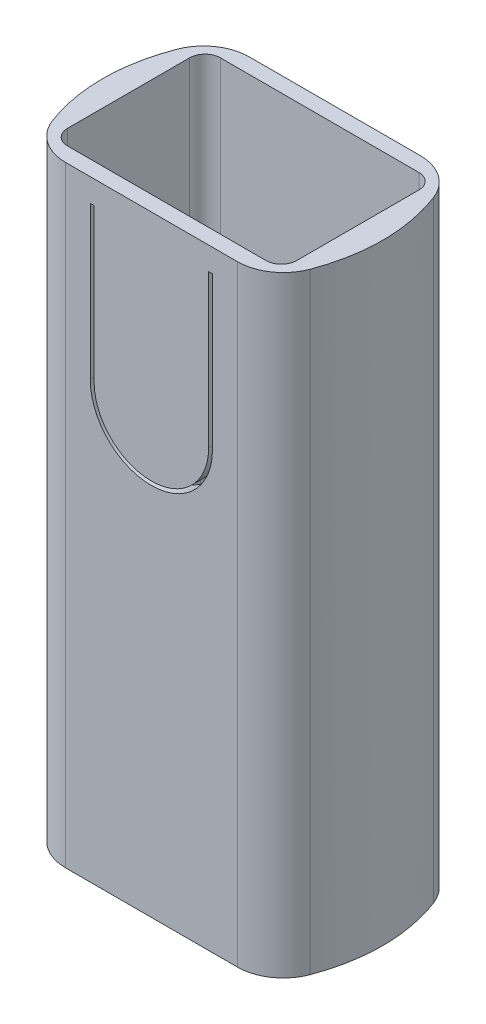
SolidWorks part; units mm, degrees
ref_plane "Front Plane" through (0, 0, 0) normal (0, 0, 1) x (1, 0, 0)
ref_plane "Top Plane" through (0, 0, 0) normal (0, 1, 0) x (1, 0, 0)
ref_plane "Right Plane" through (0, 0, 0) normal (1, 0, 0) x (0, 0, -1)
ref_plane "Plane1" through (0, 58, 0) normal (0, 1, 0) x (1, 0, 0)
sketch "Sketch8" plane through (0, 58, 0) normal (0, 1, 0) x (1, 0, 0)
  line L0 (-13, -10) -> (13, -10)
  line L1 (-15, -8) -> (-15, 8)
  line L2 (-13, 10) -> (13, 10)
  line L3 (15, -8) -> (15, 8)
  line L5 (-15, 10) -> (0, 0) construction
  line L6 (-11.243, -12) -> (11.243, -12)
  line L8 (-11.1948, 12) -> (11.1948, 12)
  line L11 (-17, 12) -> (-13.8786, 9.7967) construction
  line L12 (0, -12) -> (0, 12) construction
  line L15 (0, 12) -> (0, -10) construction
  line L16 (14.2911, -9.5274) -> (15, -10) construction
  line L17 (0, 0) -> (17, -12) construction
  arc A0 (15, -8) -> (13, -10) centre (13, -8) cw
  arc A1 (-15, -8) -> (-13, -10) centre (-13, -8) ccw
  arc A8 (-13, 10) -> (-15, 8) centre (-13, 8) ccw
  arc A9 (13, 10) -> (15, 8) centre (13, 8) cw
  arc A10 (-11.1948, 12) -> (-16.8117, 8.1097) centre (-11.1948, 6) ccw
  arc A11 (-11.243, -12) -> (-16.8596, -8.1104) centre (-11.243, -6) cw
  arc A12 (11.1948, 12) -> (16.8117, 8.1097) centre (11.1948, 6) cw
  arc A13 (11.243, -12) -> (16.8596, -8.1104) centre (11.243, -6) ccw
  spline S0 degree 3 poles (-16.8596, -8.1104) (-17.8507, -5.4727) (-18.8343, 0.0284) (-17.8195, 5.4265) (-16.8117, 8.1097) knots 0.167422 0.167422 0.167422 0.167422 0.502499 0.837905 0.837905 0.837905 0.837905
  spline S1 degree 3 poles (16.8596, -8.1104) (17.8507, -5.4727) (18.8343, 0.0284) (17.8195, 5.4265) (16.8117, 8.1097) knots 0.167422 0.167422 0.167422 0.167422 0.502499 0.837905 0.837905 0.837905 0.837905
  point P0 (0, 0)
  point P19 (-15, 10)
  point P26 (0, 0)
  point P27 (-12, 9.5)
  point P28 (15, 10)
  dimension "D3" = 2
  dimension "D2" = 6
  dimension "D7" = 2
  dimension "D1" = 30
  dimension "D4" = 24
  dimension "D5" = 20
sketch "Sketch11" plane through (0, 58, 0) normal (0, 1, 0) x (1, 0, 0)
  line L10 (-13, 10) -> (13, 10) construction
  line L11 (13, 10) -> (15, 10)
  line L13 (-13, 7.4379) -> (-13, 10)
  line L14 (0, 12) -> (0, -10) construction
  line L19 (15, 10) -> (15, 6.9379)
  line L20 (15, 6.9379) -> (13.5, 6.9379)
  line L21 (13, 7.4379) -> (13, 10)
  line L22 (-15, 6.9379) -> (-13.5, 6.9379)
  line L23 (-15, 10) -> (-15, 6.9379)
  line L24 (-13, 10) -> (-15, 10)
  arc A4 (13.5, 6.9379) -> (13, 7.4379) centre (13.5, 7.4379) cw
  arc A5 (-13.5, 6.9379) -> (-13, 7.4379) centre (-13.5, 7.4379) ccw
  dimension "D1" = 0.5
extrude "Boss-Extrude4" add sketch "Sketch8" along normal blind 80
extrude "Boss-Extrude5" add sketch "Sketch11" along normal blind 57
sketch "Sketch12" plane through (0, 0, 12) normal (0, 0, 1) x (1, 0, 0)
  line L0 (0, 138) -> (0, 58) construction
  line L1 (-11.243, 138) -> (11.243, 138) construction
  line L2 (55, 58) -> (-55, 58) construction
  line L3 (0, 116.5243) -> (0, 136.5243) construction
  line L5 (7.4764, 134.9866) -> (7.4764, 114.9866)
  line L7 (-7.5236, 134.9866) -> (-7.5236, 114.9866)
  line L8 (7.4764, 134.9866) -> (7.9764, 134.9866)
  line L9 (7.9764, 134.9866) -> (7.9764, 114.9866)
  line L10 (-8.0236, 114.9866) -> (-8.0236, 134.9866)
  line L11 (-8.0236, 134.9866) -> (-7.5236, 134.9866)
  arc A0 (7.4764, 114.9866) -> (-7.5236, 114.9866) centre (-0.0236, 114.9866) cw
  arc A1 (7.9764, 114.9866) -> (-8.0236, 114.9866) centre (-0.0236, 114.9866) cw
  dimension "D3" = 0.5
  dimension "D1" = 15
  dimension "D2" = 20
  dimension "D4" = 0.5
extrude "Cut-Extrude1" cut sketch "Sketch12" against normal blind 3
